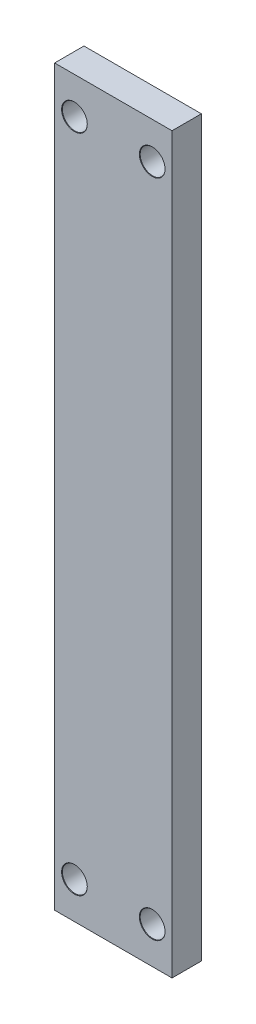
SolidWorks part; units mm, degrees
ref_plane "Alzado" through (0, 0, 0) normal (0, 0, 1) x (1, 0, 0)
ref_plane "Planta" through (0, 0, 0) normal (0, 1, 0) x (1, 0, 0)
ref_plane "Vista lateral" through (0, 0, 0) normal (1, 0, 0) x (0, 0, -1)
sketch "Croquis1" plane through (0, 0, 0) normal (0, 0, 1) x (1, 0, 0)
  line L1 (0, 0) -> (8, 0)
  line L2 (0, 0) -> (0, 50)
  line L3 (0, 50) -> (8, 50)
  line L4 (8, 0) -> (8, 50)
  dimension "D1" = 8
  dimension "D2" = 50
extrude "Saliente-Extruir1" add sketch "Croquis1" along normal blind 2
hole_wizard "Taladro de margen para M1.61" positions "Croquis3" profile "Croquis4" hole size "M1.6" standard "Ansi Metric" end condition through all
sketch "Croquis3" plane through (0, 0, 2) normal (0, 0, 1) x (1, 0, 0)
  line L0 (1.35, 47.5) -> (6.65, 47.5) construction
  line L2 (8, 50) -> (0, 50) construction
  point P0 (1.35, 47.5)
  point P2 (6.65, 47.5)
  point P12 (4, 50)
  point P13 (4, 47.5)
  dimension "D1" = 5.3
  dimension "D2" = 2.5
sketch "Croquis4" plane through (1.35, 47.5, 2) normal (1, 0, 0) x (0, -1, 0)
  line L0 (0, 0) -> (0, 2)
  line L1 (0, 2) -> (0.85, 2)
  line L2 (0.85, 2) -> (0.85, 0.0288)
  line L3 (0.85, 0.0288) -> (0.875, 0)
  line L5 (0.875, 0) -> (0, 0)
  line L6 (-0.85, 0.0288) -> (-0.875, 0) construction
  line L11 (0, -6.35) -> (0, 107.95) construction
  dimension "Diámetro de taladro hasta el siguiente" = 1.7
  dimension "Profundidad de taladro hasta el siguiente" = 2
  dimension "Diámetro de avellanado cercano" = 1.75
  dimension "Ángulo de avellanado cercano" = 82
sketch "Croquis5" plane through (0, 0, 2) normal (0, 0, 1) x (1, 0, 0)
  line L0 (1.35, 2.5) -> (6.65, 2.5) construction
  line L2 (0, 0) -> (8, 0) construction
  point P0 (1.35, 2.5)
  point P2 (6.65, 2.5)
  point P11 (4, 0)
  point P12 (4, 2.5)
  dimension "D1" = 5.3
  dimension "D2" = 2.5
hole_wizard "Taladro de margen para M1.62" positions "Croquis5" profile "Croquis6" hole size "M1.6" standard "Ansi Metric" end condition through all
sketch "Croquis6" plane through (1.35, 2.5, 2) normal (1, 0, 0) x (0, -1, 0)
  line L0 (0, 0) -> (0, 2)
  line L1 (0, 2) -> (0.85, 2)
  line L2 (0.85, 2) -> (0.85, 0.0288)
  line L3 (0.85, 0.0288) -> (0.875, 0)
  line L5 (0.875, 0) -> (0, 0)
  line L6 (-0.85, 0.0288) -> (-0.875, 0) construction
  line L11 (0, -6.35) -> (0, 107.95) construction
  dimension "Diámetro de taladro hasta el siguiente" = 1.7
  dimension "Profundidad de taladro hasta el siguiente" = 2
  dimension "Diámetro de avellanado cercano" = 1.75
  dimension "Ángulo de avellanado cercano" = 82
